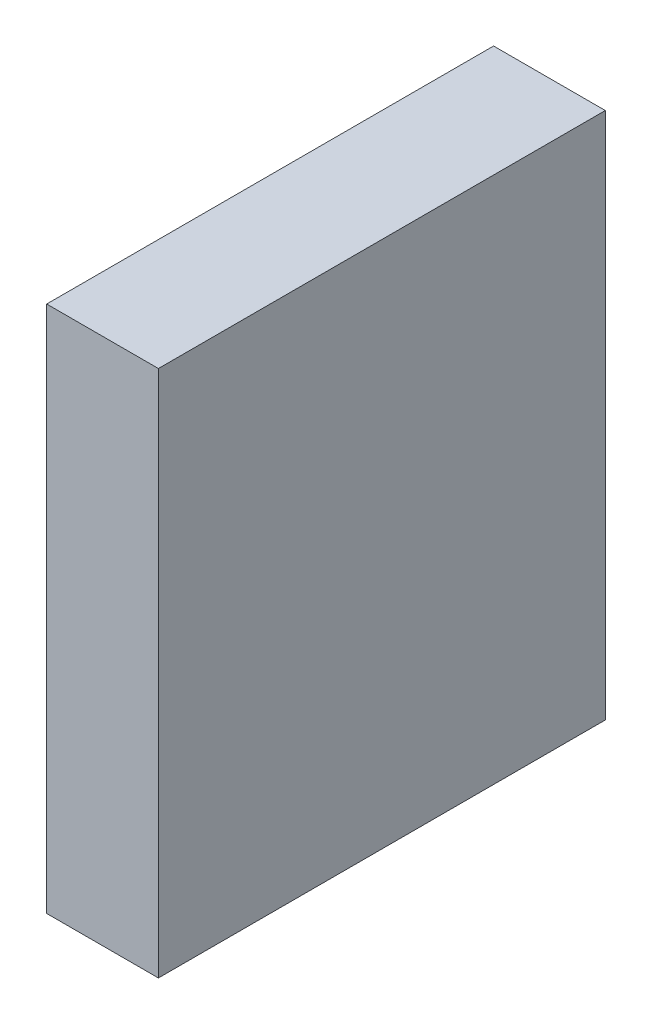
SolidWorks part; units mm, degrees
ref_plane "Front" through (0, 0, 0) normal (0, 0, 1) x (1, 0, 0)
ref_plane "Top" through (0, 0, 0) normal (0, 1, 0) x (1, 0, 0)
ref_plane "Right" through (0, 0, 0) normal (1, 0, 0) x (0, 0, -1)
sketch "Sketch1" plane through (0, 0, 0) normal (0, 1, 0) x (1, 0, 0)
  line L1 (-13.4627, -12.2685) -> (-10.9227, -12.2685)
  line L2 (-13.4627, -12.2685) -> (-13.4627, -2.1085)
  line L3 (-13.4627, -2.1085) -> (-10.9227, -2.1085)
  line L4 (-10.9227, -12.2685) -> (-10.9227, -2.1085)
extrude "Boss-Extrude1" add sketch "Sketch1" along normal blind 12
